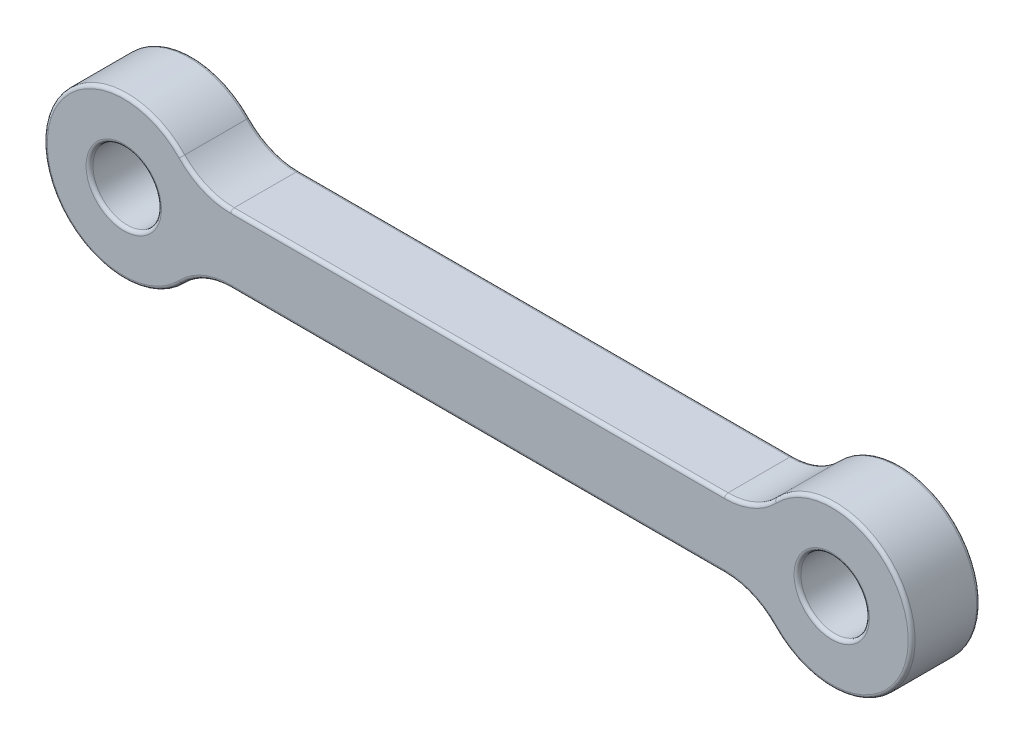
SolidWorks part; units mm, degrees
ref_plane "Front Plane" through (0, 0, 0) normal (0, 0, 1) x (1, 0, 0)
ref_plane "Top Plane" through (0, 0, 0) normal (0, 1, 0) x (1, 0, 0)
ref_plane "Right Plane" through (0, 0, 0) normal (1, 0, 0) x (0, 0, -1)
sketch "Sketch1" plane through (0, 0, 0) normal (0, 0, 1) x (1, 0, 0)
  line L0 (0, 0) -> (31, 0) construction
  line L1 (0, 3.5) -> (31, 3.5) construction
  line L2 (0, -3.5) -> (31, -3.5) construction
  line L3 (15.5, 0) -> (15.5, -3.5) construction
  line L5 (27.8377, 1.5) -> (3.1623, 1.5)
  line L6 (27.8377, 1.5) -> (27.8377, -1.5) construction
  line L7 (27.8377, -1.5) -> (3.1623, -1.5)
  line L8 (3.1623, 1.5) -> (3.1623, -1.5) construction
  line L9 (27.8377, 1.5) -> (3.1623, -1.5) construction
  line L10 (27.8377, -1.5) -> (3.1623, 1.5) construction
  arc A0 (0, 3.5) -> (0, -3.5) centre (0, 0) ccw construction
  arc A1 (31, -3.5) -> (31, 3.5) centre (31, 0) ccw construction
  circle A2 centre (0, 0) radius 1.5
  circle A3 centre (0, 0) radius 3.5
  circle A4 centre (31, 0) radius 1.5
  circle A5 centre (31, 0) radius 3.5
  point P3 (15.5, 0)
  dimension "D3" = 3
  dimension "D1" = 31
  dimension "D2" = 7
  dimension "D4" = 3
extrude "Boss-Extrude1" add sketch "Sketch1" along normal blind 3 contours A3 A2 | L7 A5 L5 A3 | A5 A4
fillet "Fillet1" radius 3 4 edges at (3.1623, -1.5, 1.5) (27.8377, -1.5, 1.5) (27.8377, 1.5, 1.5) (3.1623, 1.5, 1.5)
fillet "Fillet2" radius 0.15 20 edges at (32.5, 0, 3) (32.5, 0, 0) (3.5137, -1.7404, 3) (3.5137, -1.7404, 0) (15.5, -1.5, 3) (15.5, -1.5, 0) (27.4863, -1.7404, 3) (27.4863, -1.7404, 0) (34.5, 0, 3) (34.5, 0, 0) (27.4863, 1.7404, 3) (27.4863, 1.7404, 0) (15.5, 1.5, 3) (15.5, 1.5, 0) (3.5137, 1.7404, 3) (3.5137, 1.7404, 0) (-3.5, 0, 0) (-3.5, 0, 3) (1.5, 0, 3) (1.5, 0, 0)
